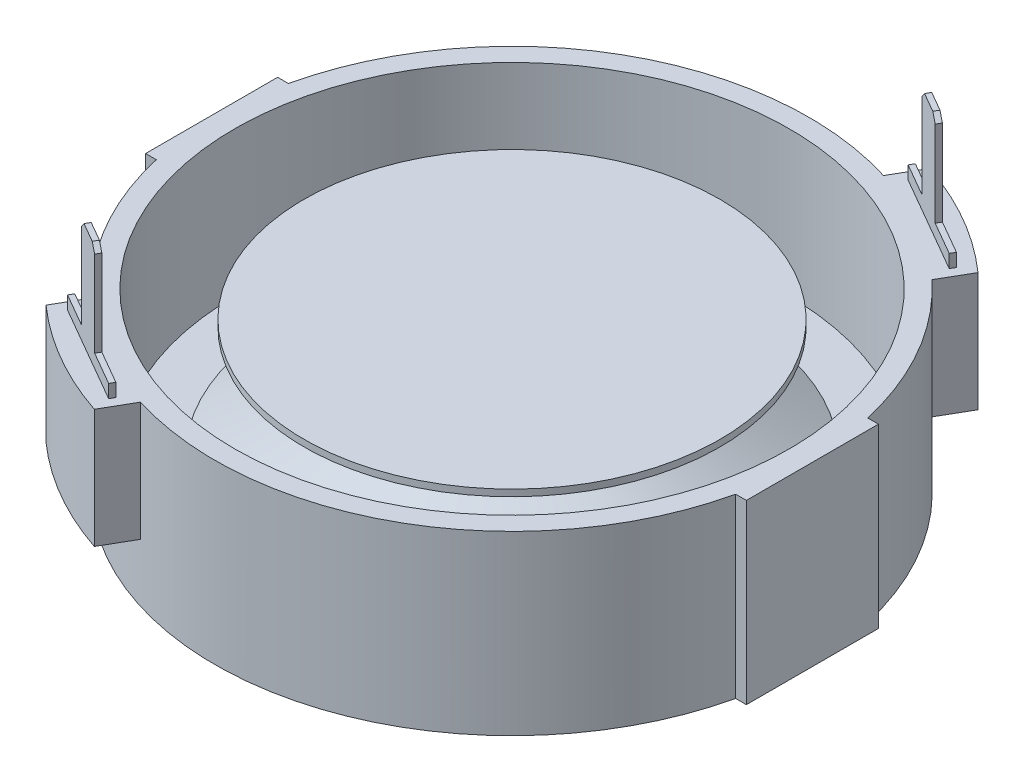
SolidWorks part; units mm, degrees
material "Полиамид ПА-6Б ТУ 6-05-988-87"
ref_plane "Спереди" through (0, 0, 0) normal (0, 0, 1) x (1, 0, 0)
ref_plane "Сверху" through (0, 0, 0) normal (0, 1, 0) x (1, 0, 0)
ref_plane "Справа" through (0, 0, 0) normal (1, 0, 0) x (0, 0, -1)
sketch "Эскиз1" plane through (0, 0, 0) normal (0, 1, 0) x (1, 0, 0)
  circle A0 centre (0, 0) radius 22.5
  dimension "D1" = 45
extrude "Бобышка-Вытянуть1" add sketch "Эскиз1" along normal blind 13.4
sketch "Эскиз5" plane through (0, 13.4, 0) normal (0, 1, 0) x (1, 0, 0)
  circle A0 centre (0, 0) radius 21.0016
  dimension "D1" = 42.0032
extrude "Вырез-Вытянуть1" cut sketch "Эскиз5" against normal blind 11
sketch "Эскиз6" plane through (0, 0, 0) normal (0, -1, 0) x (-1, 0, 0)
  circle A0 centre (0, 0) radius 8
  dimension "D1" = 16
extrude "Вырез-Вытянуть2" cut sketch "Эскиз6" against normal blind 3
sketch "Эскиз8" plane through (0, 13.4, 0) normal (0, 1, 0) x (1, 0, 0)
  line L0 (7.9173, 23.7132) -> (6.6386, 21.4984)
  line L1 (0, 0) -> (13.8032, 23.9079) construction
  line L2 (16.5776, 18.7132) -> (15.2988, 16.4984)
  line L3 (0, 14.8355) -> (0, 0) construction
  line L4 (14.3383, 0) -> (0, 0) construction
  line L5 (-7.9173, -23.7132) -> (-6.6386, -21.4984)
  line L6 (-16.5776, -18.7132) -> (-15.2988, -16.4984)
  circle A0 centre (0, 0) radius 22.5 construction
  arc A1 (-15.2988, -16.4984) -> (-6.6386, -21.4984) centre (0, 0) ccw
  arc A2 (-16.5776, -18.7132) -> (-7.9173, -23.7132) centre (0, 0) ccw
  arc A3 (15.2988, 16.4984) -> (6.6386, 21.4984) centre (0, 0) ccw
  arc A4 (16.5776, 18.7132) -> (7.9173, 23.7132) centre (0, 0) ccw
  point P20 (0, 0)
  dimension "D1" = 50
  dimension "D2" = 10
  dimension "D3" = 30
  dimension "D4" = 2
extrude "Бобышка-Вытянуть6" add sketch "Эскиз8" against normal blind 9
sketch "Эскиз9" plane through (0, 13.4, 0) normal (0, 1, 0) x (1, 0, 0)
  line L0 (8.0694, 22.4766) -> (7.8694, 22.1302)
  line L1 (7.8694, 22.1302) -> (15.2306, 17.8802)
  line L2 (15.2306, 17.8802) -> (15.4306, 18.2266)
  line L3 (15.4306, 18.2266) -> (8.0694, 22.4766)
  line L4 (0, 0) -> (12.5, 21.6506) construction
  line L5 (7.9173, 23.7132) -> (6.6386, 21.4984) construction
  line L6 (0, 0) -> (11.2177, -6.4765) construction
  line L7 (-8.0694, -22.4766) -> (-15.4306, -18.2266)
  line L8 (-7.8694, -22.1302) -> (-8.0694, -22.4766)
  line L9 (-15.2306, -17.8802) -> (-7.8694, -22.1302)
  line L10 (-15.4306, -18.2266) -> (-15.2306, -17.8802)
  arc A0 (16.5776, 18.7132) -> (7.9173, 23.7132) centre (0, 0) ccw construction
  dimension "D1" = 8.5
  dimension "D2" = 0.4
  dimension "D3" = 47
extrude "Бобышка-Вытянуть7" add sketch "Эскиз9" along normal blind 1
sketch "Эскиз10" plane through (0, 14.4, 0) normal (0, 1, 0) x (1, 0, 0)
  line L0 (10.5809, 21.0266) -> (10.3809, 20.6802)
  line L1 (15.4306, 18.2266) -> (8.0694, 22.4766) construction
  line L2 (7.8694, 22.1302) -> (15.2306, 17.8802) construction
  line L3 (10.3809, 20.6802) -> (12.7191, 19.3302)
  line L4 (12.7191, 19.3302) -> (12.9191, 19.6766)
  line L5 (12.9191, 19.6766) -> (10.5809, 21.0266)
  line L6 (0, 0) -> (12.5, 21.6506) construction
  line L7 (0, 0) -> (11.9851, -6.9196) construction
  line L8 (-10.5809, -21.0266) -> (-12.9191, -19.6766)
  line L9 (-10.3809, -20.6802) -> (-10.5809, -21.0266)
  line L10 (-12.7191, -19.3302) -> (-10.3809, -20.6802)
  line L11 (-12.9191, -19.6766) -> (-12.7191, -19.3302)
  arc A0 (16.5776, 18.7132) -> (7.9173, 23.7132) centre (0, 0) ccw construction
  dimension "D1" = 2.7
extrude "Бобышка-Вытянуть8" add sketch "Эскиз10" along normal blind 7
chamfer "Фаска1" distance 0.5 angle 45 4 edges at (10.4809, 21.4, -20.8534) (12.8191, 21.4, -19.5034) (-12.8191, 21.4, 19.5034) (-10.4809, 21.4, 20.8534)
sketch "Эскиз11" plane through (0, 0, 0) normal (1, 0, 0) x (0, 0, -1)
  line L0 (0, 0) -> (0, 22.8012) construction
  line L1 (20.5, 2.4) -> (17.5, 2.4)
  line L2 (17.5, 2.4) -> (5, 9.6169)
  line L3 (5, 9.6169) -> (5, 10.9)
  line L4 (5, 10.9) -> (15.75, 10.9)
  line L5 (15.75, 10.9) -> (15.75, 11.4)
  line L6 (15.75, 11.4) -> (0, 11.4)
  line L7 (8, 2.4) -> (-8, 2.4) construction
  line L8 (20.5, 2.4) -> (20.5, 1.9)
  line L9 (20.5, 1.9) -> (17.366, 1.9)
  line L10 (17.366, 1.9) -> (4.5, 9.3282)
  line L11 (4.5, 9.3282) -> (4.5, 10.9)
  line L12 (4.5, 10.9) -> (0, 10.9)
  line L13 (0, 10.9) -> (0, 11.4)
  line L15 (16.4984, 13.4) -> (-22.5, 13.4) construction
  line L16 (22.5, 0) -> (22.5, 13.4) construction
  point P14 (0, 0)
  point P17 (0, 0)
  point P19 (0, 0)
  point P22 (0, 0)
  dimension "D1" = 0.5
  dimension "D2" = 0.5
  dimension "D3" = 3
  dimension "D4" = 2
  dimension "D5" = 0.5
  dimension "D6" = 0.5
  dimension "D7" = 2
  dimension "D8" = 150
  dimension "D9" = 5
  dimension "D10" = 31.5
revolve "Повернуть1" add sketch "Эскиз11" angle 360 about L0
sketch "Эскиз13" plane through (0, 0, 0) normal (0, -1, 0) x (1, 0, 0)
  circle A0 centre (0, 0) radius 9.5
  dimension "D1" = 19
extrude "Вырез-Вытянуть4" cut sketch "Эскиз13" against normal blind 2
sketch "Эскиз15" plane through (0, 0, 0) normal (0, -1, 0) x (1, 0, 0)
  line L0 (0, 0) -> (-13.2112, 0) construction
  line L1 (-21.9374, 5) -> (-22.75, 5)
  line L2 (-21.9374, -5) -> (-22.75, -5)
  line L3 (-22.75, 5) -> (-22.75, -5)
  line L4 (0, 0) -> (0, 11.1502) construction
  line L5 (22.75, 5) -> (22.75, -5)
  line L6 (21.9374, -5) -> (22.75, -5)
  line L7 (21.9374, 5) -> (22.75, 5)
  circle A0 centre (0, 0) radius 22.5 construction
  arc A1 (-21.9374, -5) -> (-21.9374, 5) centre (0, 0) cw
  arc A2 (21.9374, -5) -> (21.9374, 5) centre (0, 0) ccw
  dimension "D2" = 45.5
  dimension "D1" = 10
extrude "Бобышка-Вытянуть10" add sketch "Эскиз15" against normal up to surface (13.4 mm away) up to face at (0, 13.4, 21.0016)
